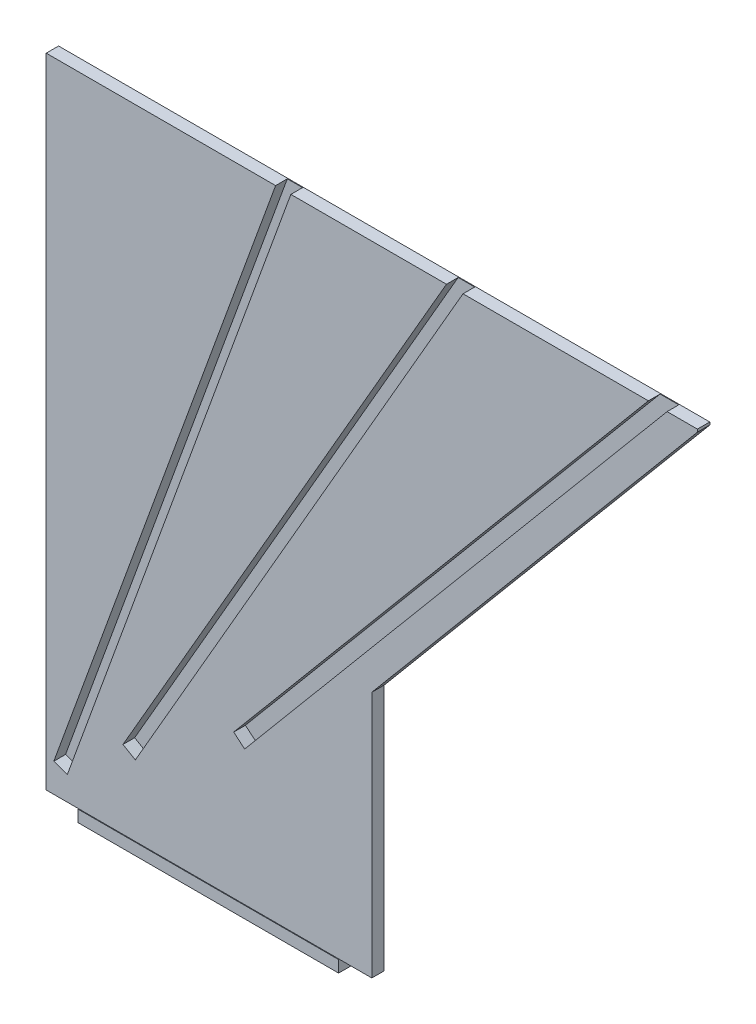
SolidWorks part; units mm, degrees
ref_plane "Front Plane" through (0, 0, 0) normal (0, 0, 1) x (1, 0, 0)
ref_plane "Top Plane" through (0, 0, 0) normal (0, 1, 0) x (1, 0, 0)
ref_plane "Right Plane" through (0, 0, 0) normal (1, 0, 0) x (0, 0, -1)
sketch "Sketch1" plane through (0, 0, 0) normal (0, 0, 1) x (1, 0, 0)
  line L0 (-37.265, -36.6025) -> (12.735, 50)
  line L1 (-50, 50) -> (50, 50)
  line L2 (-50, 50) -> (-50, -50)
  line L3 (-50, -50) -> (50, -50)
  line L4 (50, 50) -> (50, -50)
  line L5 (-50, 50) -> (50, -50) construction
  line L6 (-50, -50) -> (50, 50) construction
  line L7 (-45, -50) -> (-40, -50)
  line L8 (-47.805, -43.9693) -> (-13.603, 50)
  line L9 (-20.3688, -26.6044) -> (43.91, 50)
  line L12 (42.474, 50) -> (-21.2114, -25.8974)
  line L15 (-14.7736, 50) -> (-48.8387, -43.593)
  line L16 (-12.4324, 50) -> (-46.7713, -44.3455)
  line L17 (45.3459, 50) -> (-19.5261, -27.3115)
  line L20 (11.4649, 50) -> (-38.2176, -36.0525)
  line L21 (-50, 50) -> (-150, 50)
  line L22 (-150, 50) -> (-150, -50)
  line L23 (-150, -50) -> (-50, -50)
  line L24 (-50, -50) -> (-50, 50)
  line L25 (-150, 50) -> (-50, 50)
  line L26 (50, 50) -> (50, 150)
  line L27 (-150, 50) -> (-150, 150)
  line L28 (-50, 50) -> (50, 150)
  line L29 (-50, -50) -> (-45, -50)
  line L30 (14.0052, 50) -> (-36.3123, -37.1525)
  line L34 (-13.603, 50) -> (-47.805, -43.9693)
  line L35 (-47.805, -43.9693) -> (-46.7713, -44.3455)
  line L36 (-47.805, -43.9693) -> (-48.8387, -43.593)
  line L37 (12.735, 50) -> (-37.265, -36.6025)
  line L38 (-37.265, -36.6025) -> (-36.3123, -37.1525)
  line L39 (-37.265, -36.6025) -> (-38.2176, -36.0525)
  line L40 (43.91, 50) -> (-20.3688, -26.6044)
  line L41 (-20.3688, -26.6044) -> (-19.5261, -27.3115)
  line L42 (-20.3688, -26.6044) -> (-21.2114, -25.8974)
  line L43 (0, -50) -> (0, -10)
  line L44 (0, -10) -> (50, 49.5877)
  line L45 (0, -50) -> (-5, -50)
  line L48 (-50, -50) -> (-45, -50)
  line L50 (-45, -50) -> (-45, -48)
  line L51 (-45, -48) -> (-5, -48)
  line L52 (-5, -48) -> (-5, -50)
  line L53 (-45, -48) -> (-50, -48)
  line L54 (-5, -48) -> (0, -48)
  point P0 (0, 0)
  dimension "D1" = 100
  dimension "D2" = 100
  dimension "D3" = 60
  dimension "D4" = 50
  dimension "D5" = 70
  dimension "D6" = 1.1
  dimension "D7" = 50
extrude "Boss-Extrude1" add sketch "Sketch1" along normal blind 1.9
ref_plane "Plane1" through (0, 0, 0) normal (0, 0, -1) x (-1, 0, 0)
sketch "Sketch2" plane through (0, 0, 0) normal (0, 0, -1) x (-1, 0, 0)
  line L0 (-45.3459, 50) -> (-42.474, 50)
  line L1 (-42.474, 50) -> (21.2114, -25.8974)
  line L2 (21.2114, -25.8974) -> (19.5261, -27.3115)
  line L3 (19.5261, -27.3115) -> (-45.3459, 50)
  line L4 (-14.0052, 50) -> (36.3123, -37.1525)
  line L5 (36.3123, -37.1525) -> (38.2176, -36.0525)
  line L6 (38.2176, -36.0525) -> (-11.4649, 50)
  line L7 (-11.4649, 50) -> (-14.0052, 50)
  line L8 (12.4324, 50) -> (14.7736, 50)
  line L9 (14.7736, 50) -> (48.8387, -43.593)
  line L10 (48.8387, -43.593) -> (46.7713, -44.3455)
  line L11 (46.7713, -44.3455) -> (12.4324, 50)
extrude "Boss-Extrude5" add sketch "Sketch2" against normal blind 0.1
ref_plane "Plane2" through (0, 0, 1.9) normal (0, 0, 1) x (1, 0, 0)
sketch "Sketch6" plane through (0, 0, 1.9) normal (0, 0, 1) x (1, 0, 0)
  line L0 (-45, -48) -> (-5, -48)
  line L1 (-5, -48) -> (-5, -50)
  line L2 (-5, -50) -> (-45, -50)
  line L3 (-45, -50) -> (-45, -48)
extrude "Boss-Extrude6" add sketch "Sketch6" along normal blind 0.1
chamfer "Chamfer2" distance 0.2 angle 45 4 edges at (-45, -50, 1) (-25, -50, 2) (-5, -50, 1) (-25, -50, 0)
